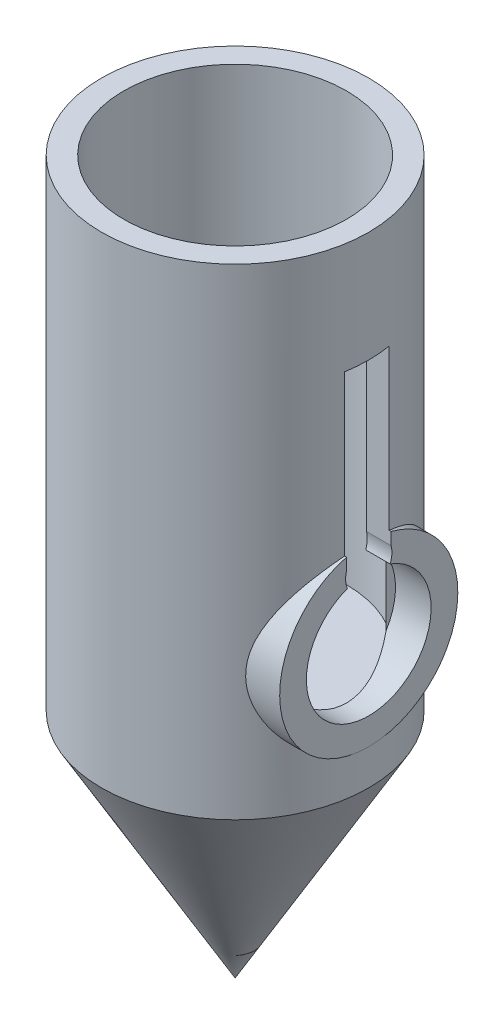
SolidWorks part; units mm, degrees
material "ABS"
ref_plane "Front" through (0, 0, 0) normal (0, 0, 1) x (1, 0, 0)
ref_plane "Top" through (0, 0, 0) normal (0, 1, 0) x (1, 0, 0)
ref_plane "Right" through (0, 0, 0) normal (1, 0, 0) x (0, 0, -1)
sketch "Sketch1" plane through (0, 0, 0) normal (1, 0, 0) x (0, 0, -1)
  line L0 (-9.525, 0) -> (-7.9375, 0)
  line L1 (-7.9375, 0) -> (-7.9375, -30.4922)
  line L2 (0, 0) -> (0, 26.3018) construction
  line L3 (-7.9375, -30.4922) -> (0, -30.4922)
  line L4 (-9.525, 0) -> (-9.525, -34.3022)
  line L5 (-9.525, -34.3022) -> (0, -50.8)
  line L6 (0, -50.8) -> (0, -30.4922)
  dimension "D1" = 15.875
  dimension "D2" = 3.81
  dimension "D3" = 30
  dimension "D4" = 19.05
  dimension "D6" = 50.8
revolve "mainBody" add sketch "Sketch1" angle 360 about L2
ref_plane "Tangent" through (9.525, 0, 0) normal (1, 0, 0) x (0, 0, -1)
sketch "sensor" plane through (9.525, 0, 0) normal (1, 0, 0) x (0, 0, -1)
  line L1 (0, -31.7622) -> (0, -34.3022) construction
  line L2 (9.525, -34.3022) -> (-9.525, -34.3022) construction
  circle A0 centre (0, -25.4122) radius 6.35
  dimension "D1" = 12.7
  dimension "D2" = 2.54
extrude "Boss-Extrude1" add sketch "sensor" against normal up to surface (2.4255 mm away)
sketch "Sketch4" plane through (9.525, 0, 0) normal (1, 0, 0) x (0, 0, -1)
  circle A0 centre (0, -25.4122) radius 4.445
  dimension "D1" = 8.89
extrude "Cut-Extrude1" cut sketch "Sketch4" against normal blind 2.54
sketch "Sketch5" plane through (9.525, 0, 0) normal (1, 0, 0) x (0, 0, -1)
  line L1 (-1.5875, -7.8862) -> (1.5875, -7.8862)
  line L2 (-1.5875, -7.8862) -> (-1.5875, -20.1327)
  line L3 (-1.5875, -20.5862) -> (1.5875, -20.5862) construction
  line L4 (1.5875, -7.8862) -> (1.5875, -20.1327)
  line L5 (-1.5875, -7.8862) -> (1.5875, -20.5862) construction
  line L6 (-1.5875, -20.5862) -> (1.5875, -7.8862) construction
  arc A0 (-1.5875, -20.1327) -> (1.5875, -20.1327) centre (0, -20.5862) ccw
  point P2 (0, -14.2362)
  dimension "D1" = 3.302
  dimension "D2" = 4.826
  dimension "D3" = 3.175
  dimension "D4" = 12.7
extrude "Cut-Extrude2" cut sketch "Sketch5" against normal offset from surface (3.175 mm away) 0.635 up to face at (6.985, -25.4122, 4.1076) offset beyond the face yes
